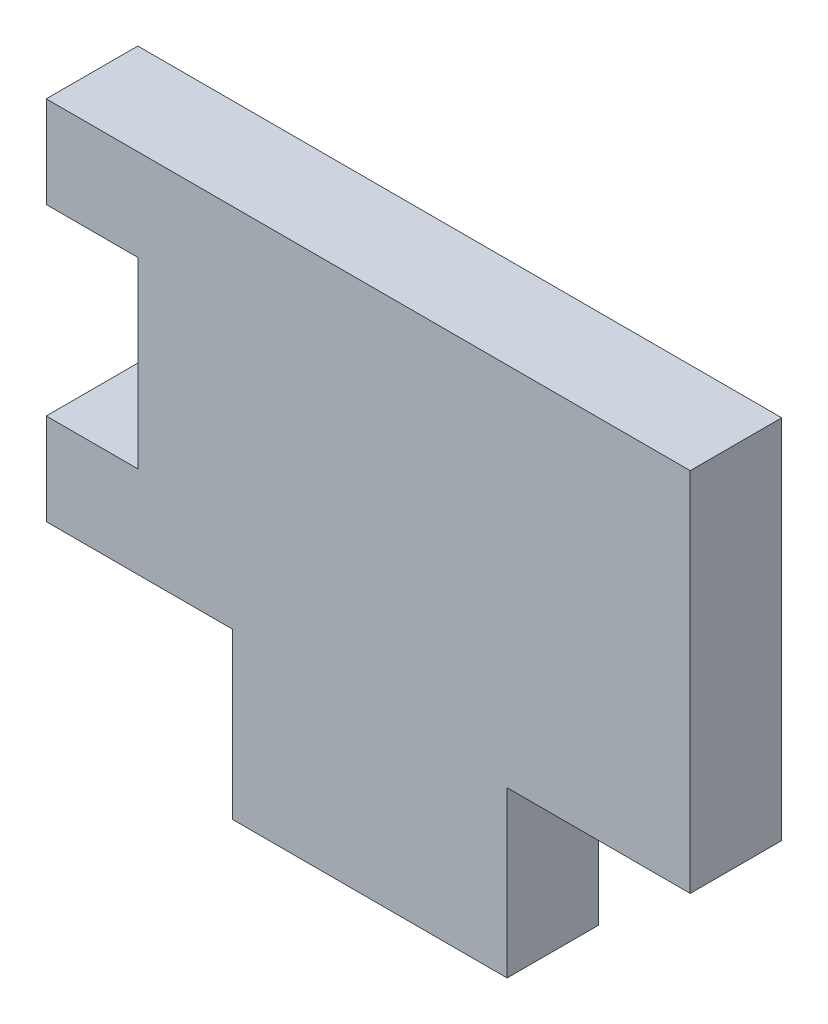
SolidWorks part; units mm, degrees
ref_plane "Front Plane" through (0, 0, 0) normal (0, 0, 1) x (1, 0, 0)
ref_plane "Top Plane" through (0, 0, 0) normal (0, 1, 0) x (1, 0, 0)
ref_plane "Right Plane" through (0, 0, 0) normal (1, 0, 0) x (0, 0, -1)
sketch "Sketch1" plane through (0, 0, 0) normal (0, 0, 1) x (1, 0, 0)
  line L1 (10, -6.0626) -> (25, -6.0626)
  line L2 (-0.174, 2.9374) -> (-0.174, 7.9374)
  line L3 (-0.174, 22.9374) -> (35, 22.9374)
  line L4 (35, 2.9374) -> (35, 22.9374)
  line L8 (10, 2.9374) -> (10, -6.0626)
  line L9 (17.5, 5.5) -> (17.5, 30.4808) construction
  line L10 (25, 2.9374) -> (25, -6.0626)
  line L11 (4.826, 17.9374) -> (-0.174, 17.9374)
  line L12 (4.826, 7.9374) -> (4.826, 17.4374)
  line L13 (4.826, 7.9374) -> (-0.174, 7.9374)
  line L15 (-0.174, 2.9374) -> (10, 2.9374)
  line L19 (25, 2.9374) -> (35, 2.9374)
  line L22 (4.826, 17.9374) -> (4.826, 17.4374)
  line L23 (-0.174, 17.9374) -> (-0.174, 22.9374)
  dimension "D1" = 20
  dimension "D2" = 10
  dimension "D4" = 10
  dimension "D5" = 15
  dimension "D6" = 5
  dimension "D7" = 5
  dimension "D3" = 9
extrude "Boss-Extrude1" add sketch "Sketch1" along normal blind 5
